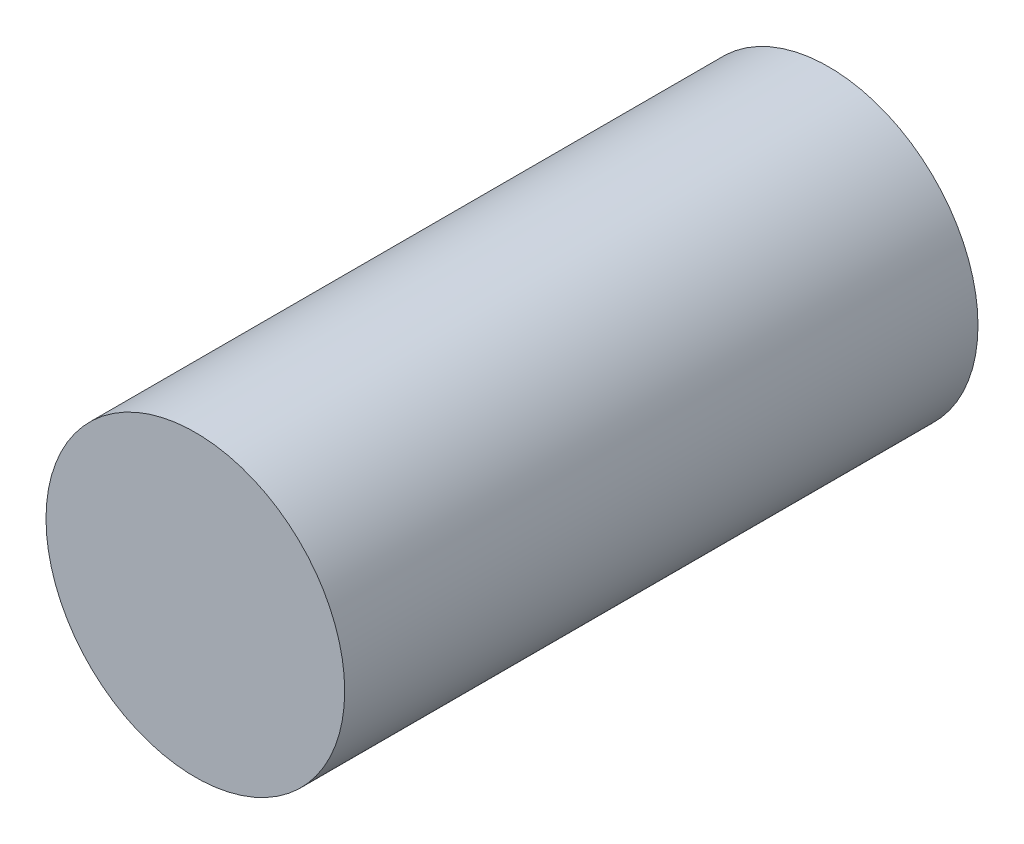
SolidWorks part; units mm, degrees
ref_plane "Front Plane" through (0, 0, 0) normal (0, 0, 1) x (1, 0, 0)
ref_plane "Top Plane" through (0, 0, 0) normal (0, 1, 0) x (1, 0, 0)
ref_plane "Right Plane" through (0, 0, 0) normal (1, 0, 0) x (0, 0, -1)
sketch "Sketch1" plane through (0, 0, 0) normal (0, 0, 1) x (1, 0, 0)
  circle A0 centre (0, 0) radius 1.778
  dimension "D1" = 3.556
extrude "Boss-Extrude1" add sketch "Sketch1" along normal blind 7.54
